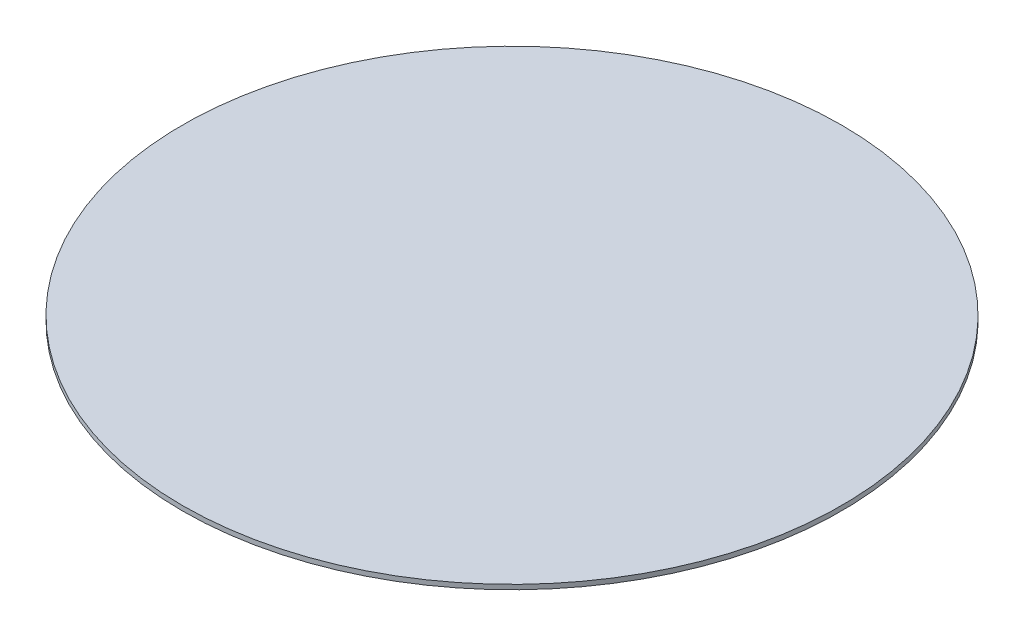
SolidWorks part; units mm, degrees
ref_plane "Ön Düzlem" through (0, 0, 0) normal (0, 0, 1) x (1, 0, 0)
ref_plane "Üst Düzlem" through (0, 0, 0) normal (0, 1, 0) x (1, 0, 0)
ref_plane "Sağ Düzlem" through (0, 0, 0) normal (1, 0, 0) x (0, 0, -1)
sketch "Çizim1" plane through (0, 0, 0) normal (0, 1, 0) x (1, 0, 0)
  circle A0 centre (0, 0) radius 350
  dimension "D1" = 700
extrude "Yükseklik-Ekstrüzyon1" add sketch "Çizim1" along normal blind 5
